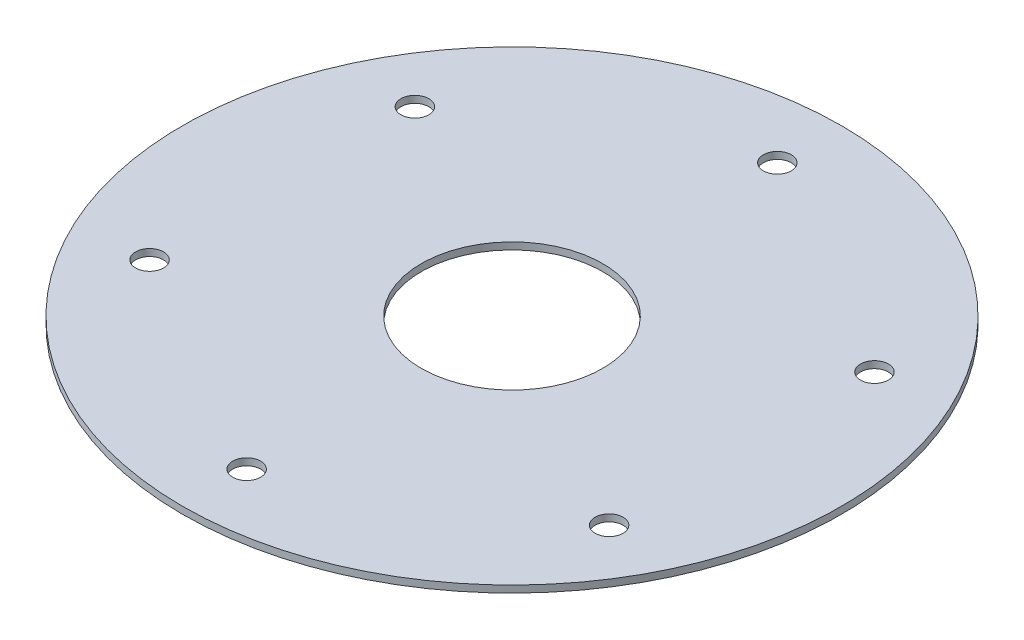
SolidWorks part; units mm, degrees
ref_plane "Front Plane" through (0, 0, 0) normal (0, 0, 1) x (1, 0, 0)
ref_plane "Top Plane" through (0, 0, 0) normal (0, 1, 0) x (1, 0, 0)
ref_plane "Right Plane" through (0, 0, 0) normal (1, 0, 0) x (0, 0, -1)
sketch "Sketch1" plane through (0, 0, 0) normal (0, 1, 0) x (1, 0, 0)
  circle A0 centre (0, 0) radius 47.2
  dimension "D1" = 94.4
extrude "Boss-Extrude1" add sketch "Sketch1" along normal blind 1
sketch "Sketch2" plane through (0, 1, 0) normal (0, 1, 0) x (1, 0, 0)
  circle A0 centre (0, 0) radius 13
  dimension "D1" = 26
extrude "Cut-Extrude1" cut sketch "Sketch2" against normal blind 1
sketch "Sketch4" plane through (0, 1, 0) normal (0, 1, 0) x (1, 0, 0)
  line L0 (0, 50.52) -> (0, -52.0568) construction
  circle A0 centre (0, 38) radius 2
  dimension "D1" = 4
  dimension "D2" = 38
extrude "Cut-Extrude3" cut sketch "Sketch4" against normal through all
pattern_circular "CirPattern1" count 6 over 360 about axis through (0, 0, 0) along (0, 1, 0) of "Cut-Extrude3"
